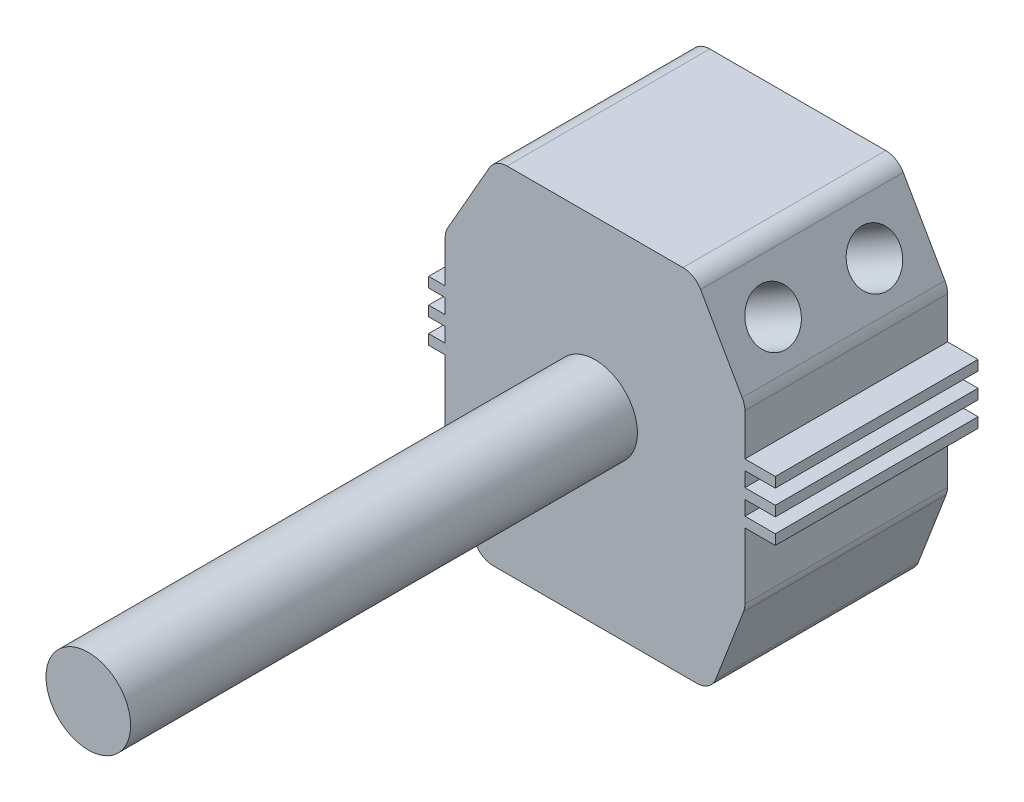
SolidWorks part; units mm, degrees
material "PVC Rigid"
ref_plane "Front Plane" through (0, 0, 0) normal (0, 0, 1) x (1, 0, 0)
ref_plane "Top Plane" through (0, 0, 0) normal (0, 1, 0) x (1, 0, 0)
ref_plane "Right Plane" through (0, 0, 0) normal (1, 0, 0) x (0, 0, -1)
sketch "Sketch1" plane through (0, 0, 0) normal (0, 0, 1) x (1, 0, 0)
  line L0 (-20.6841, -48.3451) -> (19.3159, -48.3451) construction
  line L1 (-0.6841, -48.3451) -> (-0.6841, -98.3451) construction
  line L2 (-0.6841, -98.3451) -> (19.3159, -98.3451) construction
  line L3 (-0.6841, -98.3451) -> (-20.6841, -98.3451) construction
  line L4 (19.3159, -48.3451) -> (19.3159, -98.3451) construction
  line L5 (-20.6841, -48.3451) -> (-20.6841, -98.3451) construction
  line L6 (7.9955, -56.4738) -> (-9.3637, -56.4738)
  line L7 (-11.1002, -57.4815) -> (-15.2061, -64.6668)
  line L8 (-15.4696, -65.6591) -> (-15.4696, -82.1773)
  line L9 (-15.3363, -82.8953) -> (-12.5909, -90.0332)
  line L10 (-10.7242, -91.3153) -> (9.356, -91.3153)
  line L11 (13.9681, -82.8953) -> (11.2227, -90.0332)
  line L12 (14.1014, -65.6591) -> (14.1014, -82.1773)
  line L13 (9.732, -57.4815) -> (13.8379, -64.6668)
  arc A0 (-15.4696, -65.6591) -> (-15.2061, -64.6668) centre (-13.4696, -65.6591) cw
  arc A1 (-15.4696, -82.1773) -> (-15.3363, -82.8953) centre (-13.4696, -82.1773) ccw
  arc A2 (-12.5909, -90.0332) -> (-10.7242, -91.3153) centre (-10.7242, -89.3153) ccw
  arc A3 (11.2227, -90.0332) -> (9.356, -91.3153) centre (9.356, -89.3153) cw
  arc A4 (14.1014, -65.6591) -> (13.8379, -64.6668) centre (12.1014, -65.6591) ccw
  arc A5 (-9.3637, -56.4738) -> (-11.1002, -57.4815) centre (-9.3637, -58.4738) ccw
  arc A6 (9.732, -57.4815) -> (7.9955, -56.4738) centre (7.9955, -58.4738) ccw
  arc A7 (14.1014, -82.1773) -> (13.9681, -82.8953) centre (12.1014, -82.1773) cw
  point P15 (-0.6841, -91.3153)
  point P16 (-0.6841, -56.4738)
  point P18 (-15.4696, -65.1279)
  point P21 (-15.4696, -82.5487)
  point P24 (-12.0978, -91.3153)
  point P27 (10.7296, -91.3153)
  point P32 (-10.5243, -56.4738)
  point P35 (9.1561, -56.4738)
  dimension "D1" = 2
  dimension "D3" = 2
  dimension "D6" = 2
  dimension "D7" = 2
  dimension "D2" = 50
  dimension "D4" = 20
  dimension "D5" = 20
extrude "Boss-Extrude1" add sketch "Sketch1" along normal blind 20
sketch "Sketch2" plane through (0, 0, 20) normal (0, 0, 1) x (1, 0, 0)
  circle A0 centre (-0.6778, -72.8589) radius 4.175
  dimension "D1" = 8.35
extrude "Boss-Extrude2" add sketch "Sketch2" along normal blind 50
sketch "Sketch3" plane through (-17.4248, -9.9571, 0) normal (0.8682, 0.4961, 0) x (0, 0, -1)
  line L0 (-20, -63.012) -> (-20, -54.7363) construction
  line L1 (0, -63.012) -> (0, -54.7363) construction
  line L2 (-70, -58.748) -> (-70, -67.098) construction
  circle A0 centre (-15, -59.0744) radius 2.5
  circle A1 centre (-5, -59.0744) radius 2.5
  dimension "D1" = 5
  dimension "D2" = 5
  dimension "D3" = 5
  dimension "D4" = 5
extrude "Cut-Extrude1" cut sketch "Sketch3" against normal blind 20
sketch "Sketch4" plane through (16.3934, -9.3677, 0) normal (-0.8682, 0.4961, 0) x (0, 0, 1)
  line L0 (0, -55.4151) -> (0, -63.6908) construction
  line L1 (20, -55.4151) -> (20, -63.6908) construction
  circle A0 centre (5, -59.4808) radius 2.5
  circle A1 centre (15, -59.4808) radius 2.5
  dimension "D1" = 5
  dimension "D2" = 5
  dimension "D3" = 5
  dimension "D4" = 5
extrude "Cut-Extrude2" cut sketch "Sketch4" against normal blind 20
sketch "Sketch5" plane through (14.1014, 0, 0) normal (1, 0, 0) x (0, 0, -1)
  line L0 (-20, -69.7695) -> (0, -69.7695)
  line L1 (-20, -68.6839) -> (-20, -77.0339) construction
  line L2 (0, -82.1773) -> (0, -65.6591) construction
  line L3 (0, -69.7695) -> (0, -70.7695)
  line L4 (0, -70.7695) -> (-20, -70.7695)
  line L5 (-20, -70.7695) -> (-20, -69.7695)
  line L7 (-20, -72.2288) -> (0, -72.2288)
  line L8 (0, -72.2288) -> (0, -73.2288)
  line L9 (0, -73.2288) -> (-20, -73.2288)
  line L10 (-20, -73.2288) -> (-20, -72.2288)
  line L11 (-20, -74.6635) -> (0, -74.6635)
  line L12 (0, -74.6635) -> (0, -75.6635)
  line L13 (0, -75.6635) -> (-20, -75.6635)
  line L14 (-20, -82.1773) -> (-20, -65.6591) construction
  line L15 (-20, -75.6635) -> (-20, -74.6635)
  dimension "D1" = 1
  dimension "D2" = 1
  dimension "D3" = 1
extrude "Boss-Extrude3" add sketch "Sketch5" along normal blind 3
mirror "Mirror1" about plane through (0, 0, 0) normal (1, 0, 0) of "Boss-Extrude3"
